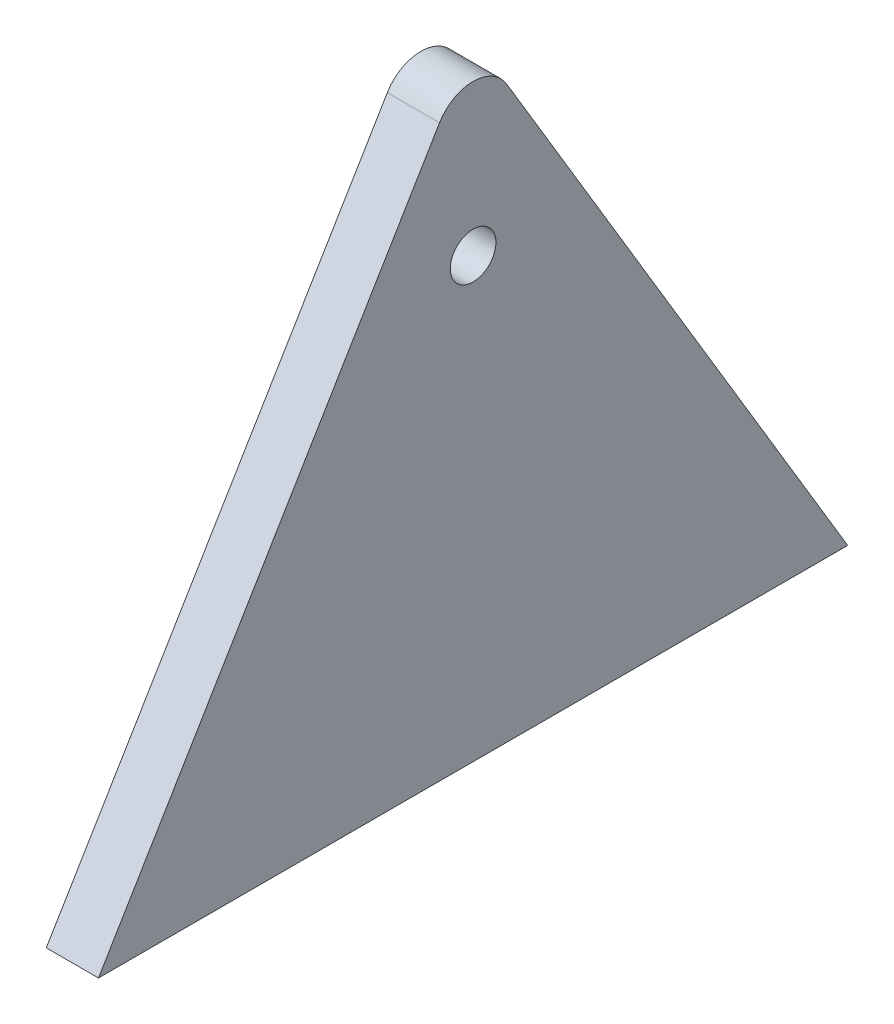
SolidWorks part; units mm, degrees
material "Pine"
ref_plane "Front Plane" through (0, 0, 0) normal (0, 0, 1) x (1, 0, 0)
ref_plane "Top Plane" through (0, 0, 0) normal (0, 1, 0) x (1, 0, 0)
ref_plane "Right Plane" through (0, 0, 0) normal (1, 0, 0) x (0, 0, -1)
sketch "Sketch1" plane through (0, 0, 0) normal (1, 0, 0) x (0, 0, -1)
  line L0 (0, 0) -> (0, 152.4) construction
  line L1 (0, 152.4) -> (-91.1608, 0)
  line L2 (-91.1608, 0) -> (91.1608, 0)
  line L3 (0, 152.4) -> (91.1608, 0)
  dimension "D1" = 152.4
  dimension "D2" = 30.887
extrude "Boss-Extrude1" add sketch "Sketch1" along normal blind 12.7
fillet "Fillet1" radius 9.525 1 edges at (6.35, 152.4, 0)
sketch "Sketch2" plane through (0, 0, 0) normal (1, 0, 0) x (0, 0, -1)
  line L0 (0, 0) -> (0, 106.68) construction
  circle A0 centre (0, 106.68) radius 5.5562
  dimension "D2" = 11.1125
  dimension "D1" = 106.68
extrude "Cut-Extrude3" cut sketch "Sketch2" against normal through all and the other way through all
